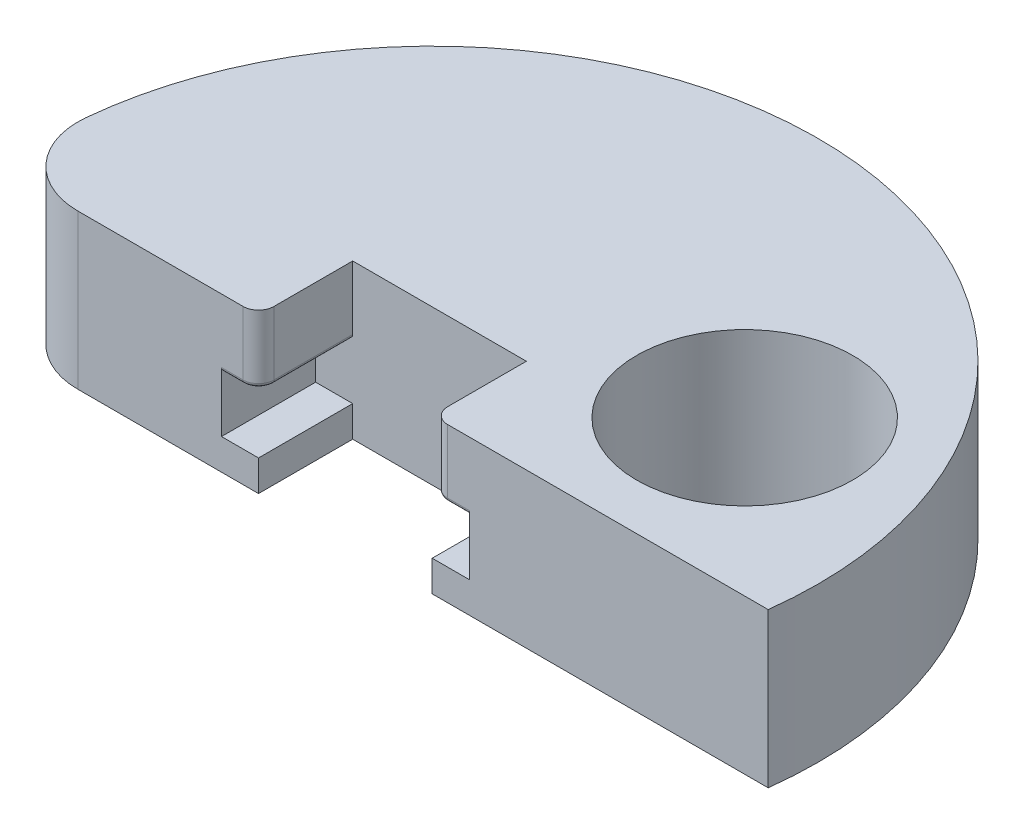
SolidWorks part; units mm, degrees
ref_plane "Front Plane" through (0, 0, 0) normal (0, 0, 1) x (1, 0, 0)
ref_plane "Top Plane" through (0, 0, 0) normal (0, 1, 0) x (1, 0, 0)
ref_plane "Right Plane" through (0, 0, 0) normal (1, 0, 0) x (0, 0, -1)
sketch "Sketch1" plane through (0, 0, 0) normal (0, 1, 0) x (1, 0, 0)
  circle A0 centre (0, 0) radius 50
  dimension "D1" = 50
extrude "Boss-Extrude1" add sketch "Sketch1" along normal blind 20
sketch "Sketch13" plane through (0, 0, 0) normal (0, -1, 0) x (1, 0, 0)
  line L0 (-16.4, 0) -> (-16.4, -6.1)
  line L1 (-16.4, -5.25) -> (-16.4, 5.25) construction
  line L2 (-20.35, -6.1) -> (-15.55, -6.1) construction
  line L3 (-16.4, -6.1) -> (5.25, -6.1)
  line L4 (6.1, -5.25) -> (6.1, -6.1)
  line L5 (5.25, -6.1) -> (10.05, -6.1) construction
  line L6 (6.1, -6.1) -> (5.25, -6.1)
  line L7 (6.1, -5.25) -> (6.1, 6.1)
  line L8 (10.05, 6.1) -> (5.25, 6.1) construction
  line L9 (6.1, 6.1) -> (-16.4, 6.1)
  line L10 (-15.55, 6.1) -> (-20.35, 6.1) construction
  line L11 (-16.4, 6.1) -> (-16.4, 0)
  line L12 (-16.4, -6.1) -> (6.1, 6.1) construction
  line L13 (6.1, -6.1) -> (-16.4, 6.1) construction
sketch "Sketch14" plane through (0, 0, 0) normal (0, -1, 0) x (1, 0, 0)
  line L0 (-16.4, -6.1) -> (6.1, 6.1) construction
  line L1 (6.1, -6.1) -> (-16.4, 6.1) construction
  line L2 (6.1, 6.1) -> (-16.4, 6.1)
  line L3 (6.1, 6.1) -> (6.1, -6.1)
  line L4 (6.1, -6.1) -> (-16.4, -6.1)
  line L5 (-16.4, 6.1) -> (-16.4, -6.1)
  line L6 (6.1, 6.1) -> (-16.4, -6.1) construction
  line L7 (6.1, -6.1) -> (-16.4, 6.1) construction
  point P0 (-5.15, 0)
  point P1 (-5.15, 0)
  point P10 (-5.15, 0)
  point P11 (-5.15, 0)
  dimension "D1" = 22.5
  dimension "D2" = 12.2
sketch "Sketch15" plane through (0, 0, 0) normal (0, -1, 0) x (1, 0, 0)
  line L0 (-21.2, 6.1) -> (-21.2, 45.2831)
  line L1 (10.9, 6.1) -> (10.05, 48.9796)
  line L2 (-21.2, 6.1) -> (10.9, 6.1)
  circle A0 centre (0, 0) radius 50 construction
  arc A1 (-21.2, 45.2831) -> (10.05, 48.9796) centre (0, 0) cw
extrude "Cut-Extrude3" cut sketch "Sketch15" against normal through all
extrude "Cut-Extrude4" cut sketch "Sketch14" against normal through all
sketch "Sketch16" plane through (0, 0, 0) normal (0, -1, 0) x (1, 0, 0)
  line L0 (-21.2, 6.1) -> (-21.2, -6.1)
  line L1 (-21.2, 6.1) -> (-16.4, 6.1)
  line L2 (10.9, -6.1) -> (10.9, 6.1)
  line L3 (10.9, 6.1) -> (6.1, 6.1)
  line L4 (-16.4, 6.1) -> (-16.4, -6.1)
  line L5 (-16.4, -6.1) -> (-21.2, -6.1)
  line L6 (6.1, 6.1) -> (6.1, -6.1)
  line L7 (6.1, -6.1) -> (10.9, -6.1)
extrude "Cut-Extrude5" cut sketch "Sketch16" against normal blind 11.25
sketch "Sketch17" plane through (0, 0, 0) normal (0, -1, 0) x (1, 0, 0)
  circle A0 centre (8.75, 0) radius 0.5
  circle A1 centre (-19.05, 0) radius 0.5
  dimension "D1" = 1
  dimension "D2" = 1
extrude "Cut-Extrude7" cut sketch "Sketch17" against normal blind 0.4 from surface at -11.25 starting at face at (8.5, 11.25, 0)
sketch "Sketch18" plane through (0, 0, 0) normal (0, -1, 0) x (-1, 0, 0)
  line L0 (-10.9, -6.1) -> (-49.6265, -6.1)
  line L1 (-10.9, -6.1) -> (49.6265, -6.1)
  arc A0 (21.2, -45.2831) -> (-10.05, -48.9796) centre (0, 0) ccw construction
  arc A1 (49.6265, -6.1) -> (-49.6265, -6.1) centre (0, 0) cw
extrude "Cut-Extrude8" cut sketch "Sketch18" against normal through all
fillet "Fillet1" radius 2 2 edges at (-16.4, 15.625, 6.1) (6.1, 15.625, 6.1)
fillet "Fillet2" radius 0.5 6 edges at (-19.8, 11.25, 6.1) (-16.9858, 11.25, 5.5142) (6.1, 11.25, -1) (6.6858, 11.25, 5.5142) (-16.4, 11.25, -1) (9.5, 11.25, 6.1)
sketch "Sketch19" plane through (0, 0, 0) normal (0, -1, 0) x (-1, 0, 0)
  line L0 (16.4, 6.1) -> (-6.1, -6.1) construction
  point P0 (5.15, 0)
sketch "Sketch4" plane through (0, 20, 0) normal (0, 1, 0) x (1, 0, 0)
  line L0 (8.1, -6.1) -> (49.6265, -6.1) construction
  circle A0 centre (26.5855, 13.9) radius 14
  dimension "D1" = 28
  dimension "D2" = 20
  dimension "D3" = 30
extrude "Cut-Extrude2" cut sketch "Sketch4" against normal through all
sketch "Sketch20" plane through (0, 0, 0) normal (0, -1, 0) x (1, 0, 0)
  line L0 (-21.2, -6.1) -> (-16.4, -6.1)
  line L1 (-21.2, -6.1) -> (-21.2, 6.1)
  line L2 (-21.2, 6.1) -> (-16.4, 6.1)
  line L3 (-16.4, 6.1) -> (-16.4, -6.1)
  line L4 (10.9, -6.1) -> (6.1, -6.1)
  line L5 (6.1, -6.1) -> (6.1, 6.1)
  line L6 (6.1, 6.1) -> (10.9, 6.1)
  line L7 (10.9, 6.1) -> (10.9, -6.1)
  point P0 (-16.4, -6.1)
extrude "Boss-Extrude2" add sketch "Sketch20" against normal blind 4
fillet "Fillet3" radius 10 1 edges at (-49.6265, 10, 6.1)
